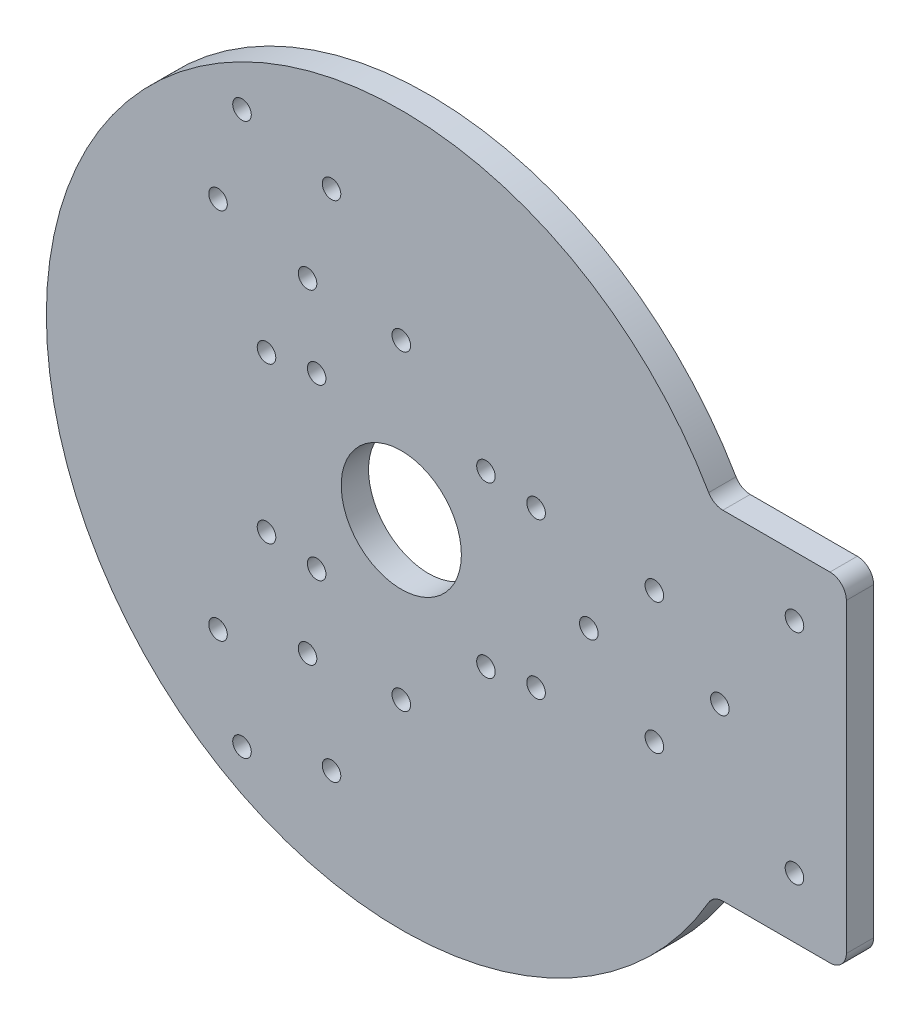
SolidWorks part; units mm, degrees
ref_plane "前视基准面" through (0, 0, 0) normal (0, 0, 1) x (1, 0, 0)
ref_plane "上视基准面" through (0, 0, 0) normal (0, 1, 0) x (1, 0, 0)
ref_plane "右视基准面" through (0, 0, 0) normal (1, 0, 0) x (0, 0, -1)
other "Configuration Table"
sketch "草图1" plane through (0, 0, 0) normal (0, 0, 1) x (1, 0, 0)
  line L0 (0, 0) -> (104.7802, 0) construction
  line L1 (81.5, -28) -> (81.5, 28)
  line L2 (78.5, 31) -> (58.8897, 31)
  line L3 (78.5, -31) -> (58.8897, -31)
  arc A0 (56.2917, 32.5) -> (56.2917, -32.5) centre (0, 0) ccw
  arc A1 (78.5, -31) -> (81.5, -28) centre (78.5, -28) ccw
  arc A2 (81.5, 28) -> (78.5, 31) centre (78.5, 28) ccw
  arc A3 (58.8897, 31) -> (56.2917, 32.5) centre (58.8897, 34) cw
  arc A4 (58.8897, -31) -> (56.2917, -32.5) centre (58.8897, -34) ccw
  point P9 (81.5, 0)
  point P10 (81.5, -31)
  point P13 (81.5, 31)
  point P16 (57.1314, 31)
  point P19 (57.1314, -31)
  dimension "D1" = 65
  dimension "D4" = 3
  dimension "D2" = 62
  dimension "D3" = 81.5
extrude "凸台-拉伸1" add sketch "草图1" along normal blind 5
sketch "草图2" plane through (0, 0, 5) normal (0, 0, 1) x (1, 0, 0)
  line L0 (0, 0) -> (58.34, 0) construction
  circle A0 centre (58.34, 0) radius 1.7
  circle A1 centre (46.34, 0) radius 1.7 construction
  circle A2 centre (46.34, -12) radius 1.7
  circle A3 centre (34.34, 0) radius 1.7
  circle A4 centre (46.34, 12) radius 1.7
  point P14 (46.34, 0)
  dimension "D2" = 3.4
  dimension "D3" = 3.4
  dimension "D1" = 46.34
  dimension "D4" = 12
  dimension "D5" = 4
extrude "切除-拉伸1" cut sketch "草图2" against normal blind 5
pattern_circular "阵列(圆周)1" count 3 over 360 about axis through (0, 0, 0) along (0, 0, 1) of "切除-拉伸1"
sketch "草图3" plane through (0, 0, 5) normal (0, 0, 1) x (1, 0, 0)
  line L0 (72, 46.6351) -> (72, -43.487) construction
  line L1 (15.5, -15.5) -> (-15.5, -15.5) construction
  line L2 (15.5, -15.5) -> (15.5, 15.5) construction
  line L3 (15.5, 15.5) -> (-15.5, 15.5) construction
  line L4 (-15.5, -15.5) -> (-15.5, 15.5) construction
  line L5 (15.5, -15.5) -> (-15.5, 15.5) construction
  line L6 (15.5, 15.5) -> (-15.5, -15.5) construction
  line L7 (0, 0) -> (90.7126, 0) construction
  circle A0 centre (0, 0) radius 11
  circle A1 centre (15.5, -15.5) radius 1.7
  circle A2 centre (15.5, 15.5) radius 1.7
  circle A3 centre (-15.5, 15.5) radius 1.7
  circle A4 centre (-15.5, -15.5) radius 1.7
  circle A5 centre (72, 20) radius 1.7
  circle A7 centre (72, -20) radius 1.7
  dimension "D1" = 22
  dimension "D3" = 3.4
  dimension "D4" = 3.4
  dimension "D2" = 31
  dimension "D5" = 72
  dimension "D6" = 40
extrude "切除-拉伸2" cut sketch "草图3" against normal blind 10
sketch "草图4" plane through (0, 0, 5) normal (0, 0, 1) x (1, 0, 0)
  line L0 (0, 0) -> (0, 28.5) construction
  circle A0 centre (0, 28.5) radius 1.7
  circle A1 centre (24.6817, 14.25) radius 1.7
  circle A2 centre (24.6817, -14.25) radius 1.7
  circle A3 centre (0, -28.5) radius 1.7
  circle A4 centre (-24.6817, -14.25) radius 1.7
  circle A5 centre (-24.6817, 14.25) radius 1.7
  point P16 (0, 0)
  dimension "D2" = 3.4
  dimension "D1" = 28.5
  dimension "D3" = 6
extrude "切除-拉伸3" cut sketch "草图4" against normal blind 10
